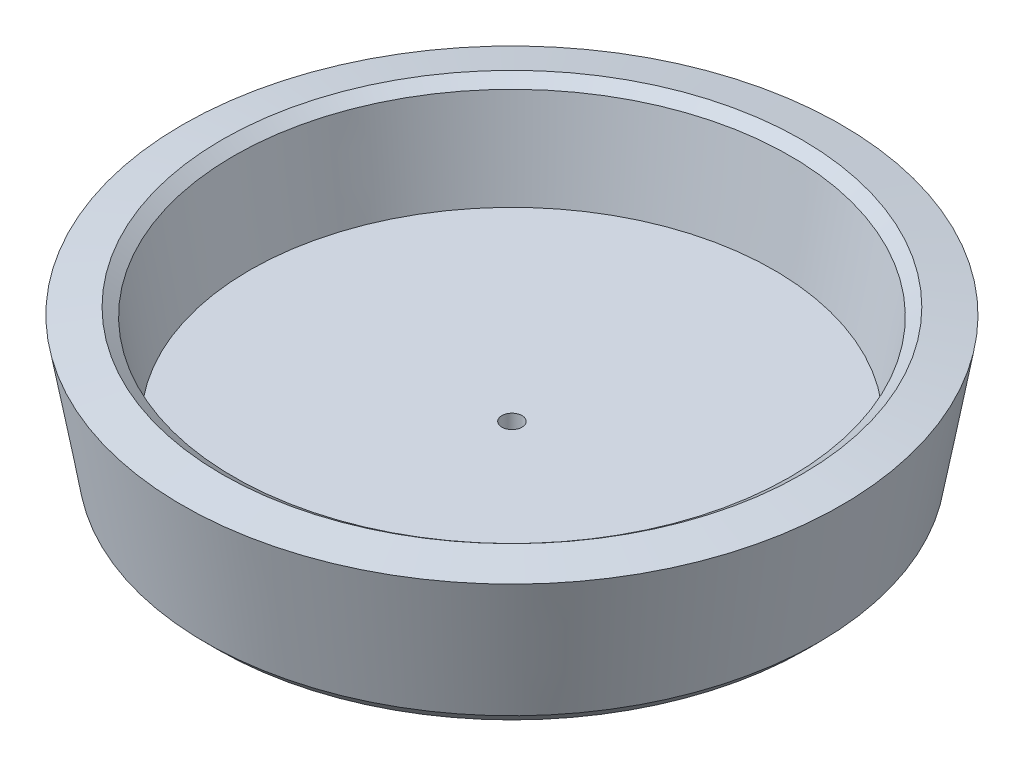
SolidWorks part; units mm, degrees
ref_plane "前视基准面" through (0, 0, 0) normal (0, 0, 1) x (1, 0, 0)
ref_plane "上视基准面" through (0, 0, 0) normal (0, 1, 0) x (1, 0, 0)
ref_plane "右视基准面" through (0, 0, 0) normal (1, 0, 0) x (0, 0, -1)
sketch "草图3" plane through (0, 0, 0) normal (0, 0, 1) x (1, 0, 0)
  line L1 (0, 0) -> (-30.1955, 0)
  line L2 (-30.1955, 0) -> (-32.6873, 14.1318)
  line L3 (-32.6873, 14.1318) -> (-27.7633, 15)
  line L4 (-27.7633, 15) -> (-26, 5)
  line L5 (-26, 5) -> (0, 5)
  line L6 (0, 5) -> (0, 0)
  dimension "D1" = 5
  dimension "D2" = 5
  dimension "D3" = 26
  dimension "D4" = 15
  dimension "D5" = 100
revolve "旋转1" add sketch "草图3" angle 360 about L6
chamfer "倒角1" distance 1 angle 45 1 edges at (-30.1955, 0, 0)
chamfer "倒角2" distance 1 angle 45 1 edges at (-27.7633, 15, 0)
sketch "草图4" plane through (0, 5, 0) normal (0, 1, 0) x (1, 0, 0)
  circle A0 centre (0, 0) radius 1
  dimension "D1" = 2
extrude "切除-拉伸1" cut sketch "草图4" against normal blind 10
